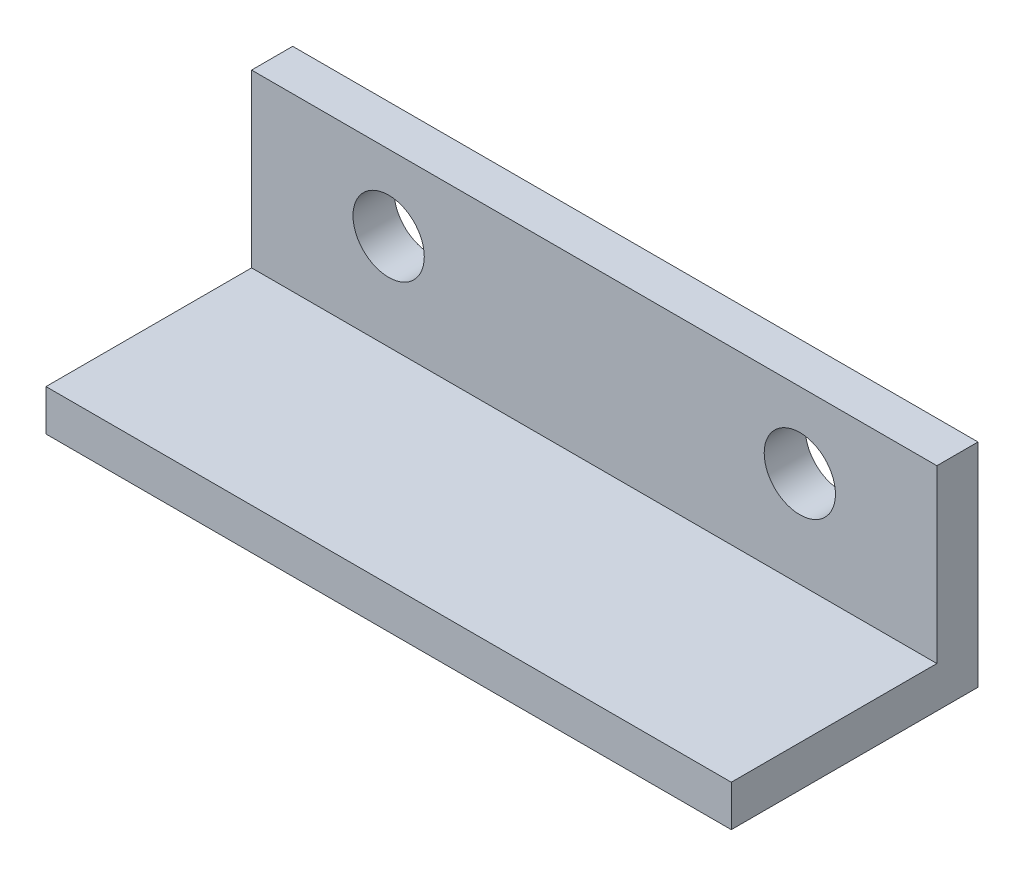
SolidWorks part; units mm, degrees
ref_plane "Ön Düzlem" through (0, 0, 0) normal (0, 0, 1) x (1, 0, 0)
ref_plane "Üst Düzlem" through (0, 0, 0) normal (0, 1, 0) x (1, 0, 0)
ref_plane "Sağ Düzlem" through (0, 0, 0) normal (1, 0, 0) x (0, 0, -1)
sketch "Çizim1" plane through (0, 0, 0) normal (0, 0, 1) x (1, 0, 0)
  line L1 (-14.3443, 6.9344) -> (35.6557, 6.9344)
  line L2 (-14.3443, 6.9344) -> (-14.3443, -11.0656)
  line L3 (-14.3443, -11.0656) -> (35.6557, -11.0656)
  line L4 (35.6557, 6.9344) -> (35.6557, -11.0656)
  circle A0 centre (-4.3443, -1.0656) radius 2.6887
  circle A1 centre (25.6557, -1.0656) radius 2.0011
  dimension "D3" = 10
  dimension "D4" = 30
  dimension "D6" = 8
  dimension "D1" = 10
  dimension "D2" = 18
extrude "Yükseklik-Ekstrüzyon1" add sketch "Çizim1" along normal blind 3 contours A0 | A1 | L4 L1 L2 L3 A1 A0
hole_wizard "M5 Helisarmal için Zıvana matkabı1" positions "Çizim2" profile "Çizim3" hole size "M5x0.8" standard "ANSI Metric" end condition up to next
sketch "Çizim2" plane through (0, 0, 0) normal (0, 0, -1) x (-1, 0, 0)
  point P0 (-25.6557, -1.0656)
  point P3 (4.3443, -1.0656)
sketch "Çizim3" plane through (25.6557, -1.0656, 0) normal (1, 0, 0) x (0, 1, 0)
  line L0 (0, 0) -> (0, 3)
  line L1 (0, 3) -> (2.6, 3)
  line L2 (2.6, 3) -> (2.6, 0)
  line L5 (2.6, 0) -> (0, 0)
  line L11 (0, -6.35) -> (0, 107.95) construction
  dimension "Thru Hole Dia." = 5.2
  dimension "Thru Hole Depth" = 3
sketch "Çizim4" plane through (0, 0, 3) normal (0, 0, 1) x (1, 0, 0)
  line L0 (35.6557, 6.9344) -> (35.6557, -11.0656) construction
  line L1 (-14.3443, -11.0656) -> (35.6557, -11.0656)
  line L2 (-14.3443, -11.0656) -> (-14.3443, -8.0656)
  line L3 (-14.3443, -8.0656) -> (35.6557, -8.0656)
  line L4 (35.6557, -11.0656) -> (35.6557, -8.0656)
  dimension "D1" = 3
extrude "Yükseklik-Ekstrüzyon2" add sketch "Çizim4" along normal blind 15
sketch "Çizim5" plane through (0, 0, 3) normal (0, 0, 1) x (1, 0, 0)
  line L0 (15.6557, 4.4344) -> (35.6557, 4.4344)
  line L2 (35.6557, 4.4344) -> (-14.3443, 4.4344)
  line L4 (35.6557, 6.9344) -> (-14.3443, 6.9344)
  line L6 (-14.3443, 4.4344) -> (-14.3443, 6.9344)
  line L8 (35.6557, 4.4344) -> (35.6557, 6.9344)
extrude "Kes-Ekstrüzyon1" cut sketch "Çizim5" against normal blind 15
